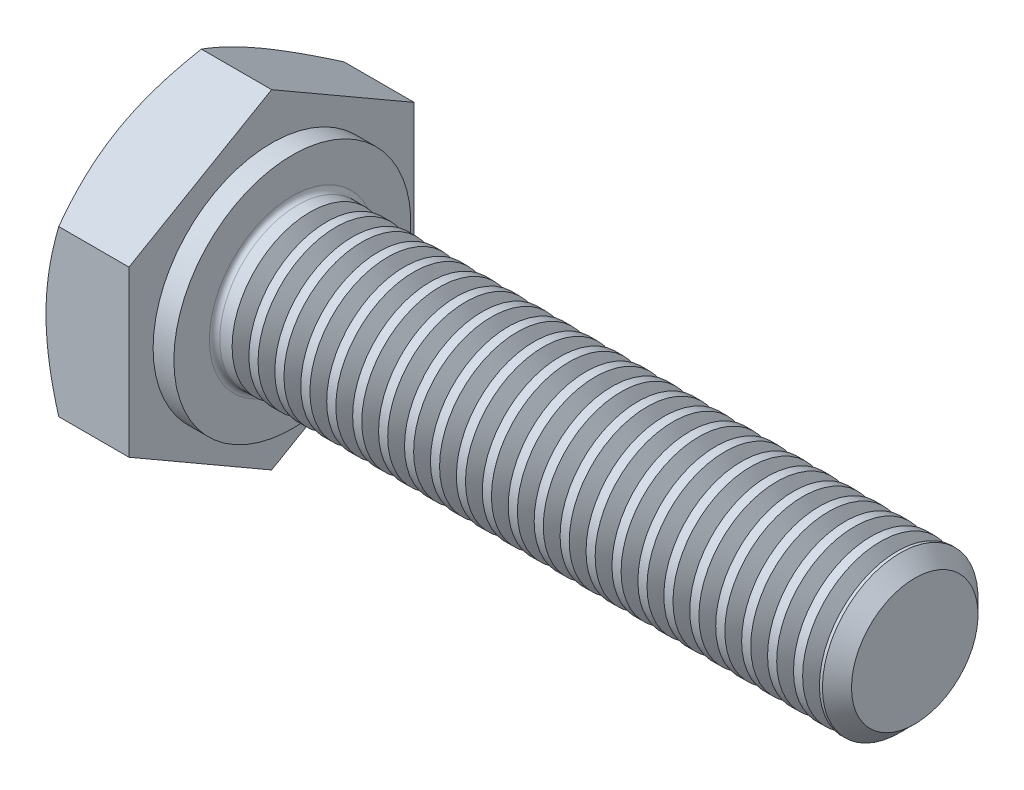
SolidWorks part; units mm, degrees
ref_plane "Front Plane" through (0, 0, 0) normal (0, 0, 1) x (1, 0, 0)
ref_plane "Top Plane" through (0, 0, 0) normal (0, 1, 0) x (1, 0, 0)
ref_plane "Right Plane" through (0, 0, 0) normal (1, 0, 0) x (0, 0, -1)
sketch "BaseHeadSke" plane through (0, 0, 0) normal (1, 0, 0) x (0, 0, -1)
  line L1 (2.75, 1.5877) -> (0, 3.1754)
  line L2 (0, 3.1754) -> (-2.75, 1.5877)
  line L3 (-2.75, 1.5877) -> (-2.75, -1.5877)
  line L4 (-2.75, -1.5877) -> (0, -3.1754)
  line L5 (0, -3.1754) -> (2.75, -1.5877)
  line L6 (2.75, -1.5877) -> (2.75, 1.5877)
  circle A0 centre (0, 0) radius 2.75 construction
  dimension "Width_flats" = 5.5
extrude "BaseHead" add sketch "BaseHeadSke" along normal blind 2
sketch "BodySke" plane through (0, 0, 0) normal (0, 0, 1) x (1, 0, 0)
  line L0 (0, 0) -> (14, 0)
  line L1 (14, 0) -> (14, 1.2195)
  line L2 (14, 1.2195) -> (13.7195, 1.5)
  line L3 (13.7195, 1.5) -> (0, 1.5)
  line L4 (0, 1.5) -> (0, 0)
  line L5 (2, 1.5877) -> (2, -1.5877) construction
  line L6 (0, 0) -> (159.3976, 0) construction
  line L7 (2, -84.3176) -> (2, 77.7215) construction
  line L8 (13.5, -21.5941) -> (13.5, 39.2994) construction
  dimension "Ang" = 45
  dimension "Length" = 12
  dimension "Diameter" = 3
  dimension "Minor_dia" = 2.439
  dimension "Thread_length" = 12
  dimension "Advance" = 0.5
revolve "BaseBody" add sketch "BodySke" angle 360 about L6
cosmetic thread "ThreadCosmetic" [suppressed] parameters "Thread_length"=12, "Thread_minor"=2.439
sketch "HeadChamferSke" plane through (0, 0, 0) normal (0, 0, 1) x (1, 0, 0)
  line L0 (0.2456, 3.1754) -> (0, 3.1754)
  line L1 (0, 3.1754) -> (0, 2.75)
  line L2 (0, 2.75) -> (0.2456, 3.1754)
  line L3 (0, 0) -> (120.9185, 0) construction
  dimension "D1" = 30
  dimension "Head_chamfer" = 5.5
revolve "HeadChamfer" cut sketch "HeadChamferSke" angle 360 about L3
sketch "BearingFaceSke" plane through (0, 0, 0) normal (0, 0, 1) x (1, 0, 0)
  line L0 (0, 0) -> (129.6443, 0) construction
  line L1 (1.6, 3.1754) -> (2, 3.1754)
  line L2 (1.6, 3.1754) -> (1.6, 2.285)
  line L3 (1.6, 2.285) -> (2, 2.285)
  line L4 (2, 3.1754) -> (2, 2.285)
  dimension "Bearing_height" = 0.4
  dimension "Dw" = 4.57
revolve "BearingFace" cut sketch "BearingFaceSke" angle 360 about L0
fillet "Fillet" radius 0.1 1 edges at (2, 0, 1.5)
sketch "ThdSchSke" plane through (0, 0, 0) normal (0, 0, 1) x (1, 0, 0)
  line L0 (13.3381, 1.8239) -> (13.3381, 1.5)
  line L1 (13.3381, 1.5) -> (13.5, 1.2195)
  line L2 (13.5, 1.2195) -> (13.6619, 1.5)
  line L3 (13.6619, 1.5) -> (13.6619, 1.8239)
  line L4 (13.6619, 1.8239) -> (13.3381, 1.8239)
  line L6 (0, 0) -> (141.9934, 0) construction
  line L7 (14, -1.2195) -> (14, 1.2195) construction
  dimension "Advance" = 0.5
  dimension "D2" = 2.439
  dimension "D3" = 3
revolve "ThreadSchematic" cut sketch "ThdSchSke" angle 360 about L6
pattern_linear "ThdSchPat" count 23 spacing 0.5 along (-1, 0, 0) of "ThreadSchematic"
equation "\"Thread_minor@ThreadCosmetic\" = \"Minor_dia@BodySke\""
equation "\"Thread_length@ThreadCosmetic\" = \"Thread_length@BodySke\""
equation "\"Head_chamfer@HeadChamferSke\" = \"Width_flats@BaseHeadSke\""
equation "\"D2@ThdSchSke\" = \"Minor_dia@BodySke\""
equation "\"D3@ThdSchSke\" = \"Diameter@BodySke\""
equation "\"Advance@ThdSchSke\" = \"Advance@BodySke\""
equation "\"D3@ThdSchPat\" = \"Advance@BodySke\""
equation "\"D1@ThdSchPat\" =  int( \"Thread_length@BodySke\"/\"Advance@BodySke\" )-1"
